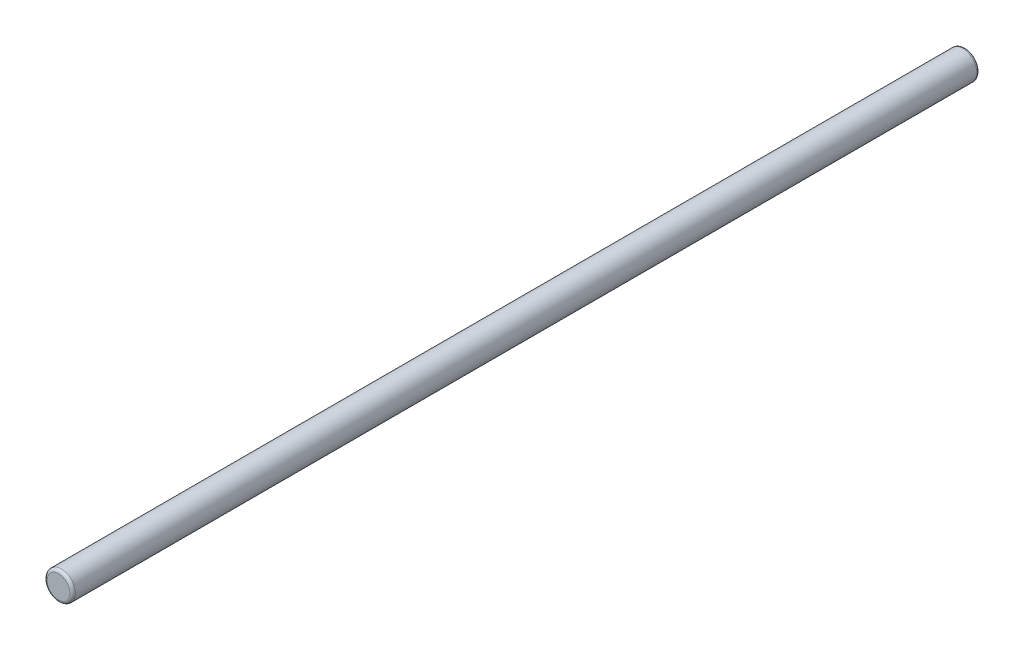
SolidWorks part; units mm, degrees
ref_plane "Plan de face" through (0, 0, 0) normal (0, 0, 1) x (1, 0, 0)
ref_plane "Plan de dessus" through (0, 0, 0) normal (0, 1, 0) x (1, 0, 0)
ref_plane "Plan de droite" through (0, 0, 0) normal (1, 0, 0) x (0, 0, -1)
sketch "Esquisse1" plane through (0, 0, 0) normal (0, 0, 1) x (1, 0, 0)
  circle A0 centre (0, 0) radius 1.25
  dimension "D1" = 2.5
extrude "Boss.-Extru.1" add sketch "Esquisse1" along normal blind 80
fillet "Congé1" radius 0.25 2 edges at (1.25, 0, 80) (1.25, 0, 0)
